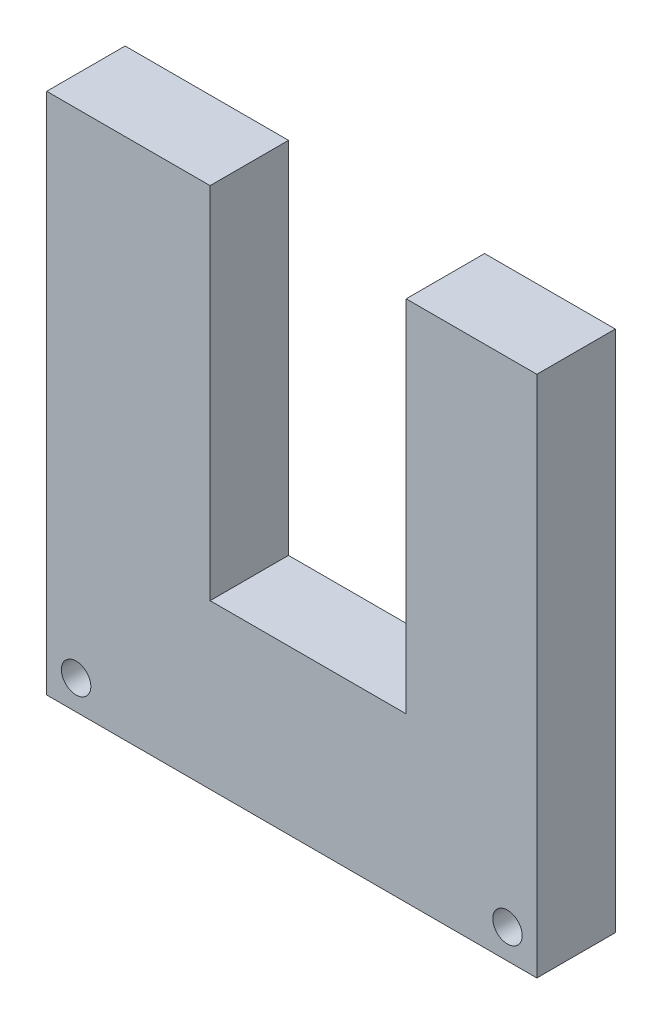
SolidWorks part; units mm, degrees
ref_plane "Front Plane" through (0, 0, 0) normal (0, 0, 1) x (1, 0, 0)
ref_plane "Top Plane" through (0, 0, 0) normal (0, 1, 0) x (1, 0, 0)
ref_plane "Right Plane" through (0, 0, 0) normal (1, 0, 0) x (0, 0, -1)
sketch "Sketch2" plane through (0, 0, 0) normal (0, 0, 1) x (1, 0, 0)
  line L0 (0, 0) -> (0, 80)
  line L1 (0, 80) -> (25, 80)
  line L2 (25, 80) -> (25, 25)
  line L3 (25, 25) -> (55, 25)
  line L4 (55, 25) -> (55, 80)
  line L5 (55, 80) -> (75, 80)
  line L6 (75, 0) -> (0, 0)
  line L7 (75, 80) -> (75, 0)
  line L8 (0, 4.5) -> (75, 4.5) construction
  circle A0 centre (70.5, 4.5) radius 2.25
  circle A1 centre (4.5, 4.5) radius 2.25
  dimension "D7" = 4.5
  dimension "D8" = 4.5
  dimension "D9" = 4.5
  dimension "D1" = 25
  dimension "D2" = 75
  dimension "D3" = 30
  dimension "D4" = 80
  dimension "D5" = 55
  dimension "D6" = 4.5
extrude "Boss-Extrude1" add sketch "Sketch2" along normal blind 12
